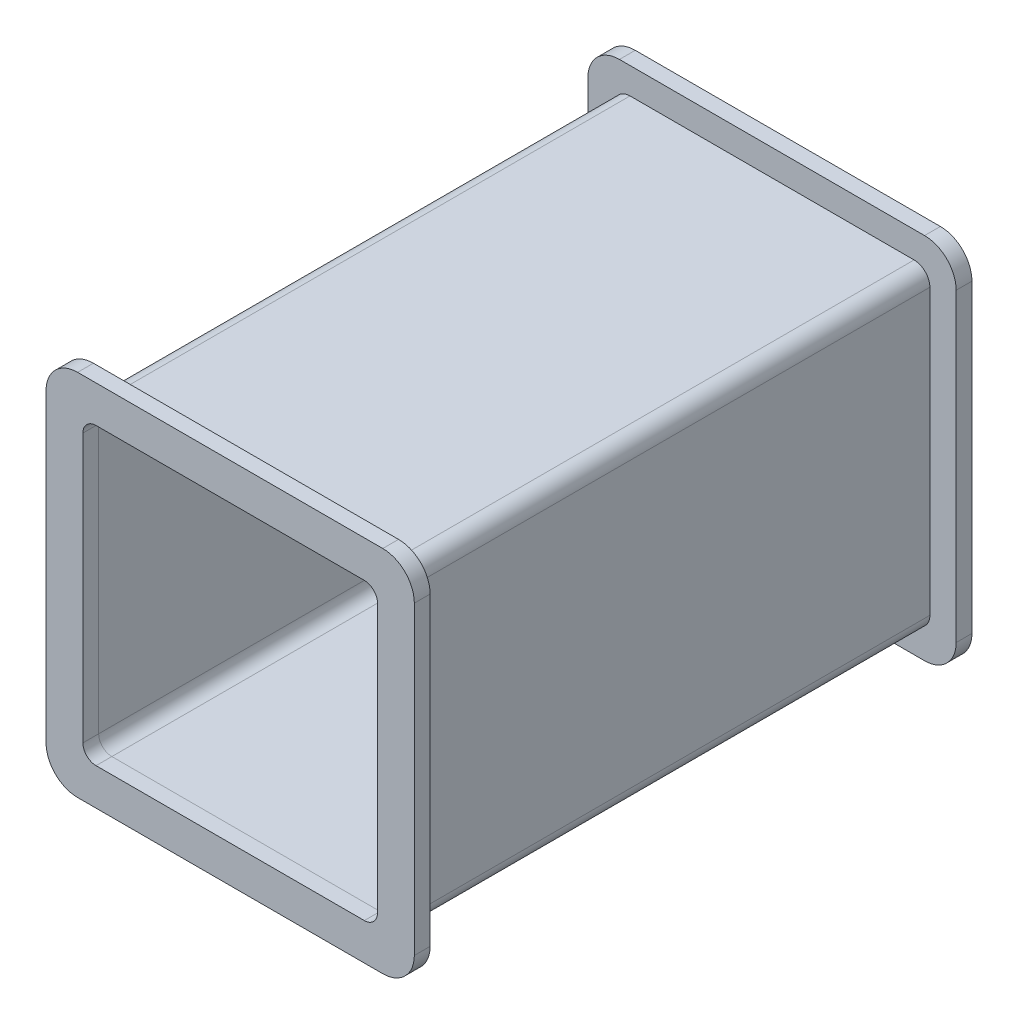
SolidWorks part; units mm, degrees
ref_plane "Front Plane" through (0, 0, 0) normal (1, 0, 0) x (0, 1, 0)
ref_plane "Top Plane" through (0, 0, 0) normal (0, 0, 1) x (0, 1, 0)
ref_plane "Right Plane" through (0, 0, 0) normal (0, 1, 0) x (-1, 0, 0)
sketch "Sketch1" plane through (0, 0, 0) normal (0, 0, 1) x (0, 1, 0)
  line L0 (0, 2.5) -> (0, 53.5)
  line L1 (2.5, 56) -> (53.5, 56)
  line L2 (56, 53.5) -> (56, 2.5)
  line L3 (53.5, 0) -> (2.5, 0)
  line L4 (1, 58) -> (55, 58)
  line L5 (-1, 63) -> (57, 63)
  line L6 (-2, 55) -> (-2, 1)
  line L7 (1, -2) -> (55, -2)
  line L8 (58, 1) -> (58, 55)
  line L10 (-7, 57) -> (-7, -1)
  line L11 (-1, -7) -> (57, -7)
  line L12 (63, -1) -> (63, 57)
  arc A0 (-7, -1) -> (-1, -7) centre (-1, -1) ccw
  arc A1 (57, -7) -> (63, -1) centre (57, -1) ccw
  arc A2 (63, 57) -> (57, 63) centre (57, 57) ccw
  arc A3 (-1, 63) -> (-7, 57) centre (-1, 57) ccw
  arc A4 (-2, 1) -> (1, -2) centre (1, 1) ccw
  arc A5 (55, -2) -> (58, 1) centre (55, 1) ccw
  arc A6 (58, 55) -> (55, 58) centre (55, 55) ccw
  arc A7 (1, 58) -> (-2, 55) centre (1, 55) ccw
  arc A8 (0, 2.5) -> (2.5, 0) centre (2.5, 2.5) ccw
  arc A9 (56, 2.5) -> (53.5, 0) centre (53.5, 2.5) cw
  arc A10 (53.5, 56) -> (56, 53.5) centre (53.5, 53.5) cw
  arc A11 (0, 53.5) -> (2.5, 56) centre (2.5, 53.5) cw
  point P31 (0, 0)
  dimension "D1" = 6
  dimension "D2" = 3
  dimension "D3" = 2.5
extrude "Boss-Extrude1" add sketch "Sketch1" against normal blind 3 contours L5 A2 L12 A1 L11 A0 L10 A3
sketch "Sketch2" plane through (0, 0, 0) normal (0, 0, 1) x (1, 0, 0)
  line L0 (-55.993, 2.4915) -> (-55.993, 53.4915)
  line L1 (-53.493, 55.9915) -> (-2.493, 55.9915)
  line L2 (0.007, 53.4915) -> (0.007, 2.4915)
  line L3 (-2.493, -0.0085) -> (-53.493, -0.0085)
  line L4 (-54.993, 57.9915) -> (-0.993, 57.9915)
  line L5 (-56.993, 62.9915) -> (1.007, 62.9915)
  line L6 (-57.993, 54.9915) -> (-57.993, 0.9915)
  line L7 (-54.993, -2.0085) -> (-0.993, -2.0085)
  line L8 (2.007, 0.9915) -> (2.007, 54.9915)
  line L9 (-62.993, 56.9915) -> (-62.993, -1.0085)
  line L10 (-56.993, -7.0085) -> (1.007, -7.0085)
  line L11 (7.007, -1.0085) -> (7.007, 56.9915)
  arc A0 (-62.993, -1.0085) -> (-56.993, -7.0085) centre (-56.993, -1.0085) ccw
  arc A1 (1.007, -7.0085) -> (7.007, -1.0085) centre (1.007, -1.0085) ccw
  arc A2 (7.007, 56.9915) -> (1.007, 62.9915) centre (1.007, 56.9915) ccw
  arc A3 (-56.993, 62.9915) -> (-62.993, 56.9915) centre (-56.993, 56.9915) ccw
  arc A4 (-57.993, 0.9915) -> (-54.993, -2.0085) centre (-54.993, 0.9915) ccw
  arc A5 (-0.993, -2.0085) -> (2.007, 0.9915) centre (-0.993, 0.9915) ccw
  arc A6 (2.007, 54.9915) -> (-0.993, 57.9915) centre (-0.993, 54.9915) ccw
  arc A7 (-54.993, 57.9915) -> (-57.993, 54.9915) centre (-54.993, 54.9915) ccw
  arc A8 (-55.993, 2.4915) -> (-53.493, -0.0085) centre (-53.493, 2.4915) ccw
  arc A9 (0.007, 2.4915) -> (-2.493, -0.0085) centre (-2.493, 2.4915) cw
  arc A10 (-2.493, 55.9915) -> (0.007, 53.4915) centre (-2.493, 53.4915) cw
  arc A11 (-55.993, 53.4915) -> (-53.493, 55.9915) centre (-53.493, 53.4915) cw
  dimension "D1" = 6
  dimension "D2" = 3
  dimension "D3" = 2.5
extrude "Boss-Extrude2" add sketch "Sketch2" along normal blind 100 contours L4 A6 L8 A5 L7 A4 L6 A7 | L0 A11 L1 A10 L2 A9 L3 A8
sketch "Sketch4" plane through (0, 0, 100) normal (0, 0, 1) x (1, 0, 0)
  line L0 (-55.9931, 2.4915) -> (-55.9931, 53.4915)
  line L1 (-53.4931, 55.9915) -> (-2.4931, 55.9915)
  line L2 (0.0069, 53.4915) -> (0.0069, 2.4915)
  line L3 (-2.4931, -0.0085) -> (-53.4931, -0.0085)
  line L4 (-54.9931, 57.9915) -> (-0.9931, 57.9915)
  line L5 (-56.9931, 62.9915) -> (1.0069, 62.9915)
  line L6 (-57.9931, 54.9915) -> (-57.9931, 0.9915)
  line L7 (-54.9931, -2.0085) -> (-0.9931, -2.0085)
  line L8 (2.0069, 0.9915) -> (2.0069, 54.9915)
  line L9 (-62.9931, 56.9915) -> (-62.9931, -1.0085)
  line L10 (-56.9931, -7.0085) -> (1.0069, -7.0085)
  line L11 (7.0069, -1.0085) -> (7.0069, 56.9915)
  arc A0 (-62.9931, -1.0085) -> (-56.9931, -7.0085) centre (-56.9931, -1.0085) ccw
  arc A1 (1.0069, -7.0085) -> (7.0069, -1.0085) centre (1.0069, -1.0085) ccw
  arc A2 (7.0069, 56.9915) -> (1.0069, 62.9915) centre (1.0069, 56.9915) ccw
  arc A3 (-56.9931, 62.9915) -> (-62.9931, 56.9915) centre (-56.9931, 56.9915) ccw
  arc A4 (-57.9931, 0.9915) -> (-54.9931, -2.0085) centre (-54.9931, 0.9915) ccw
  arc A5 (-0.9931, -2.0085) -> (2.0069, 0.9915) centre (-0.9931, 0.9915) ccw
  arc A6 (2.0069, 54.9915) -> (-0.9931, 57.9915) centre (-0.9931, 54.9915) ccw
  arc A7 (-54.9931, 57.9915) -> (-57.9931, 54.9915) centre (-54.9931, 54.9915) ccw
  arc A8 (-55.9931, 2.4915) -> (-53.4931, -0.0085) centre (-53.4931, 2.4915) ccw
  arc A9 (0.0069, 2.4915) -> (-2.4931, -0.0085) centre (-2.4931, 2.4915) cw
  arc A10 (-2.4931, 55.9915) -> (0.0069, 53.4915) centre (-2.4931, 53.4915) cw
  arc A11 (-55.9931, 53.4915) -> (-53.4931, 55.9915) centre (-53.4931, 53.4915) cw
  dimension "D1" = 6
  dimension "D2" = 3
  dimension "D3" = 2.5
extrude "Boss-Extrude3" add sketch "Sketch4" along normal blind 3 contours L5 A2 L11 A1 L10 A0 L9 A3 | L0 A11 L1 A10 L2 A9 L3 A8
sketch "Sketch5" plane through (2.007, 0, 0) normal (1, 0, 0) x (0, 1, 0)
  line L0 (0.9915, 100) -> (54.9915, 100)
  line L1 (-1.0085, 103) -> (56.9915, 103) construction
  line L2 (-1, -3) -> (57, -3) construction
  line L3 (-1, 0) -> (57, 0) construction
  dimension "D1" = 3
  dimension "D2" = 106
  dimension "D3" = 100
